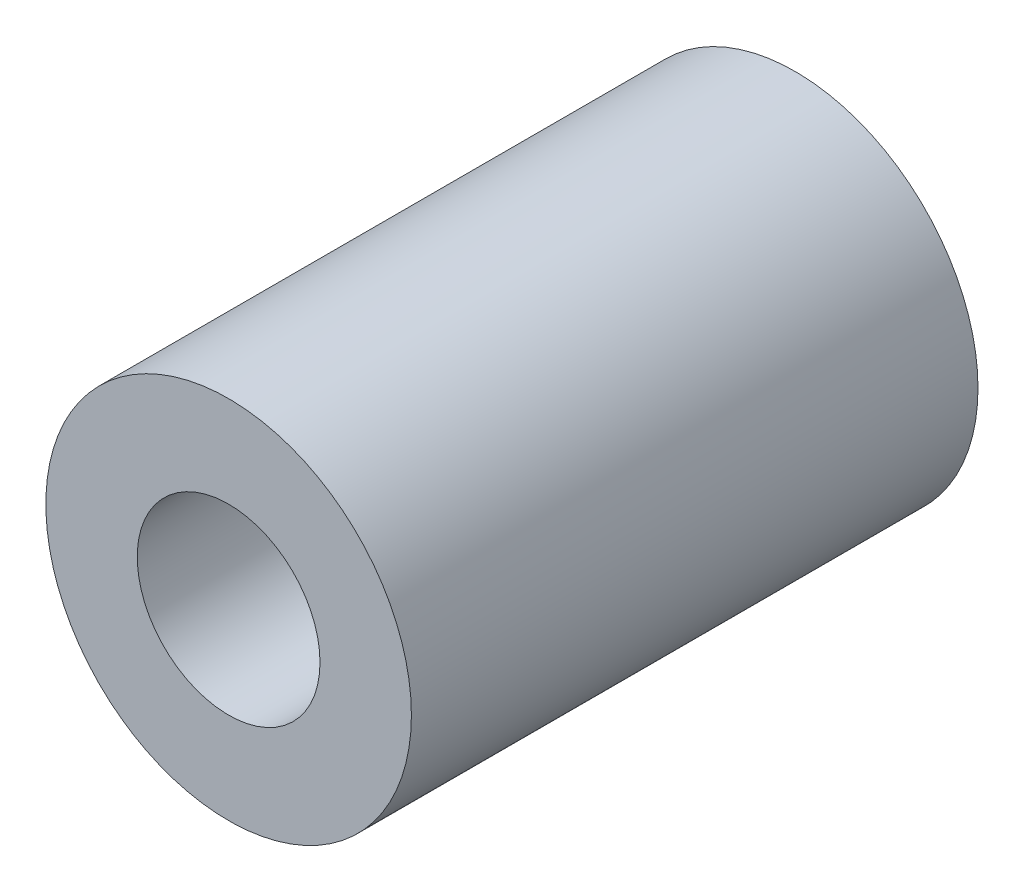
SolidWorks part; units mm, degrees
ref_plane "Alzado" through (0, 0, 0) normal (0, 0, 1) x (1, 0, 0)
ref_plane "Planta" through (0, 0, 0) normal (0, 1, 0) x (1, 0, 0)
ref_plane "Vista lateral" through (0, 0, 0) normal (1, 0, 0) x (0, 0, -1)
sketch "Croquis2" plane through (0, 0, 0) normal (0, 0, 1) x (1, 0, 0)
  circle A3 centre (0, 0) radius 10
  circle A4 centre (0, 0) radius 5
extrude "Saliente-Extruir5" add sketch "Croquis2" along normal blind 30 and the other way blind 1 contours A3 | A4
